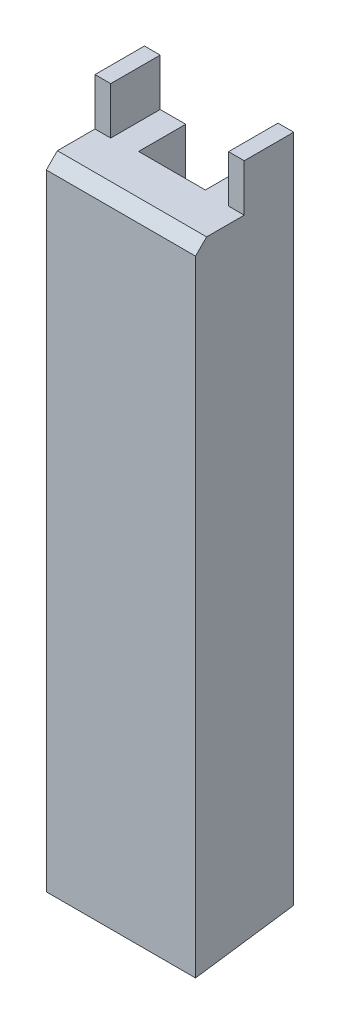
SolidWorks part; units mm, degrees
ref_plane "Front Plane" through (0, 0, 0) normal (0, 0, 1) x (1, 0, 0)
ref_plane "Top Plane" through (0, 0, 0) normal (0, 1, 0) x (1, 0, 0)
ref_plane "Right Plane" through (0, 0, 0) normal (1, 0, 0) x (0, 0, -1)
sketch "Sketch1" plane through (0, 0, 0) normal (0, 0, 1) x (1, 0, 0)
  line L1 (-9.7143, 13.1912) -> (9.2857, 13.1912)
  line L2 (-9.7143, 13.1912) -> (-9.7143, -67.8088)
  line L3 (-9.7143, -67.8088) -> (9.2857, -67.8088)
  line L4 (9.2857, 13.1912) -> (9.2857, -67.8088)
  dimension "D1" = 19
  dimension "D2" = 81
extrude "Boss-Extrude1" add sketch "Sketch1" along normal blind 12.5
sketch "Sketch2" plane through (0, 0, 0) normal (0, 0, -1) x (-1, 0, 0)
  line L0 (0.2143, 16.8694) -> (0.2143, -71.6226) construction
  line L5 (-9.2857, -67.8088) -> (-9.2857, 13.1912) construction
  line L6 (9.7143, 13.1912) -> (9.7143, -67.8088) construction
  line L7 (-9.2857, 13.1912) -> (9.7143, 13.1912) construction
  line L8 (-4.0357, 13.1912) -> (4.4643, 13.1912)
  line L9 (-4.0357, 13.1912) -> (-4.0357, -67.8088)
  line L10 (-4.0357, -67.8088) -> (4.4643, -67.8088)
  line L11 (4.4643, 13.1912) -> (4.4643, -67.8088)
  line L13 (9.7143, -67.8088) -> (-9.2857, -67.8088) construction
  dimension "D1" = 8.5
extrude "Cut-Extrude1" cut sketch "Sketch2" against normal blind 6
ref_plane "Plane1" through (0, -64.7727, -9.1032) normal (0, -0.9903, -0.1392) x (1, 0, 0)
sketch "Sketch3" plane through (0, -64.7727, -9.1032) normal (0, -0.9903, -0.1392) x (1, 0, 0)
  line L9 (-16.6295, 27.5301) -> (15.1549, 27.5301)
  line L10 (-16.6295, 27.5301) -> (-16.6295, 7.4455)
  line L11 (-16.6295, 7.4455) -> (15.1549, 7.4455)
  line L12 (15.1549, 27.5301) -> (15.1549, 7.4455)
extrude "Cut-Extrude2" cut sketch "Sketch3" along normal through all
ref_plane "Plane2" through (0, 12.8456, 12.8456) normal (0, 0.7071, 0.7071) x (-1, 0, 0)
ref_plane "Plane3" through (0, 12.1385, 12.1385) normal (0, 0.7071, 0.7071) x (-1, 0, 0)
sketch "Sketch4" plane through (0, 12.1385, 12.1385) normal (0, 0.7071, 0.7071) x (-1, 0, 0)
  line L1 (-13.8089, 2.378) -> (13.9843, 2.378)
  line L2 (-13.8089, 2.378) -> (-13.8089, -15.1192)
  line L3 (-13.8089, -15.1192) -> (13.9843, -15.1192)
  line L4 (13.9843, 2.378) -> (13.9843, -15.1192)
extrude "Cut-Extrude3" cut sketch "Sketch4" along normal through all
sketch "Sketch5" plane through (0, 13.1912, 0) normal (0, 1, 0) x (1, 0, 0)
  line L1 (-9.7143, 0) -> (-7.7143, 0)
  line L2 (-9.7143, 0) -> (-9.7143, -6.3)
  line L3 (-9.7143, -6.3) -> (-7.7143, -6.3)
  line L4 (-7.7143, 0) -> (-7.7143, -6.3)
  line L5 (9.2857, 0) -> (7.2857, 0)
  line L6 (9.2857, 0) -> (9.2857, -6.3)
  line L7 (9.2857, -6.3) -> (7.2857, -6.3)
  line L8 (7.2857, 0) -> (7.2857, -6.3)
  dimension "D1" = 2
  dimension "D2" = 6.3
  dimension "D3" = 6.3
  dimension "D4" = 2
extrude "Boss-Extrude2" add sketch "Sketch5" along normal blind 6
